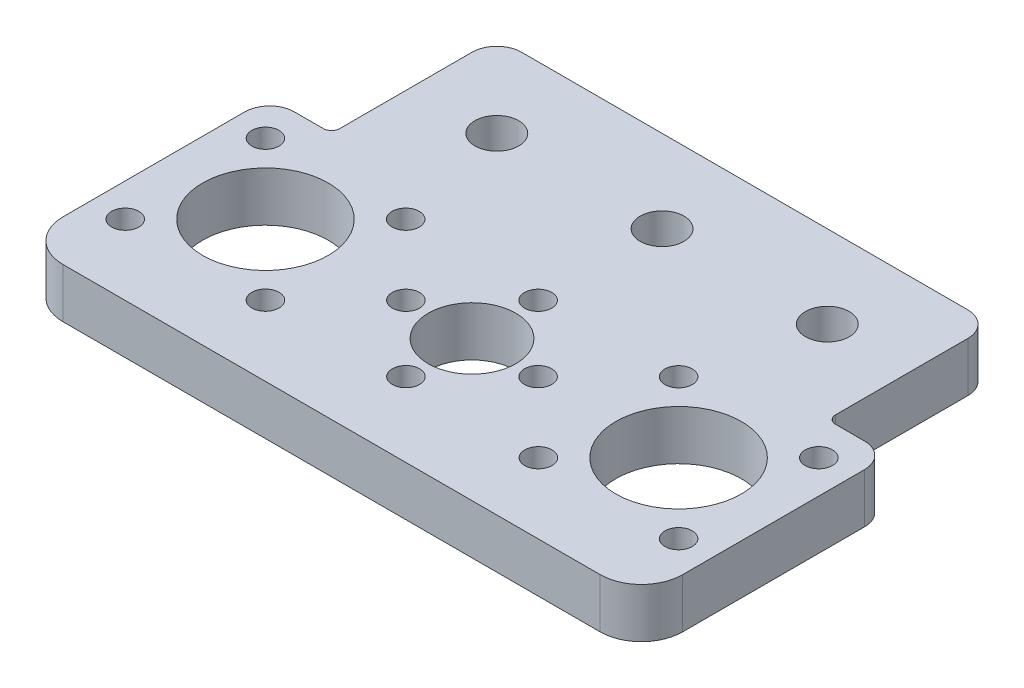
SolidWorks part; units mm, degrees
ref_plane "前视基准面" through (0, 0, 0) normal (0, 0, 1) x (1, 0, 0)
ref_plane "上视基准面" through (0, 0, 0) normal (0, 1, 0) x (1, 0, 0)
ref_plane "右视基准面" through (0, 0, 0) normal (1, 0, 0) x (0, 0, -1)
sketch "草图1" plane through (0, 0, 0) normal (0, 1, 0) x (1, 0, 0)
  line L0 (0, 80.2608) -> (0, -70.9317) construction
  line L1 (-25, 80.2608) -> (-25, -70.9317) construction
  line L2 (25, 80.2608) -> (25, -70.9317) construction
  line L3 (-49.3571, 0) -> (56.9138, 0) construction
  line L4 (-33.4853, 8.4853) -> (-16.5147, 8.4853) construction
  line L5 (-37.5, 28) -> (-37.5, -12)
  line L6 (37.5, 28) -> (37.5, -12)
  line L7 (-32.5, -17) -> (32.5, -17)
  line L8 (-49.3571, 13) -> (56.9138, 13) construction
  line L9 (-49.3571, 23) -> (56.9138, 23) construction
  line L10 (-20, 80.2608) -> (-20, -70.9317) construction
  line L11 (20, 80.2608) -> (20, -70.9317) construction
  line L12 (-32.5, 33) -> (32.5, 33)
  line L13 (-37.5, 80.2608) -> (-37.5, -70.9317) construction
  line L14 (-49.3571, -17) -> (56.9138, -17) construction
  line L15 (37.5, 80.2608) -> (37.5, -70.9317) construction
  line L16 (-49.3571, 33) -> (56.9138, 33) construction
  line L17 (-30, 80.2608) -> (-30, -70.9317) construction
  line L18 (30, 80.2608) -> (30, -70.9317) construction
  line L19 (30, 33) -> (30, 13)
  line L20 (30, 13) -> (37.5, 13)
  line L21 (-30, 33) -> (-30, 13)
  line L22 (-30, 13) -> (-37.5, 13)
  circle A0 centre (-25, 0) radius 7.6
  circle A1 centre (-25, 0) radius 12 construction
  circle A2 centre (-33.4853, 8.4853) radius 1.65
  circle A3 centre (-16.5147, 8.4853) radius 1.65
  circle A4 centre (-16.5147, -8.4853) radius 1.65
  circle A5 centre (-33.4853, -8.4853) radius 1.65
  circle A6 centre (16.5147, -8.4853) radius 1.65
  circle A7 centre (16.5147, 8.4853) radius 1.65
  circle A8 centre (33.4853, 8.4853) radius 1.65
  circle A9 centre (25, 0) radius 7.6
  circle A10 centre (33.4853, -8.4853) radius 1.65
  circle A11 centre (0, 0) radius 5.3
  circle A12 centre (0, 0) radius 8 construction
  circle A13 centre (0, 0) radius 11 construction
  circle A14 centre (0, 8) radius 1.65
  circle A15 centre (8, 0) radius 1.65
  circle A16 centre (0, -8) radius 1.65
  circle A17 centre (-8, 0) radius 1.65
  circle A18 centre (-20, 23) radius 2.65
  circle A19 centre (0, 23) radius 2.65
  circle A20 centre (20, 23) radius 2.65
  arc A21 (-37.5, -12) -> (-32.5, -17) centre (-32.5, -12) ccw
  arc A22 (32.5, -17) -> (37.5, -12) centre (32.5, -12) ccw
  arc A23 (37.5, 28) -> (32.5, 33) centre (32.5, 28) ccw
  arc A24 (-32.5, 33) -> (-37.5, 28) centre (-32.5, 28) ccw
  point P23 (-25, 0)
  point P50 (0, 0)
  dimension "D3" = 15.2
  dimension "D4" = 24
  dimension "D5" = 3.3
  dimension "D9" = 10.6
  dimension "D10" = 16
  dimension "D11" = 22
  dimension "D12" = 3.3
  dimension "D19" = 5.3
  dimension "D22" = 5
  dimension "D1" = 25
  dimension "D7" = 12.5
  dimension "D14" = 50
  dimension "D2" = 25
  dimension "D8" = 12.5
  dimension "D15" = 13
  dimension "D16" = 10
  dimension "D17" = 20
  dimension "D18" = 20
  dimension "D21" = 10
  dimension "D23" = 30
  dimension "D24" = 30
  dimension "D20" = 3
  dimension "D6" = 4
  dimension "D13" = 4
extrude "凸台-拉伸1" add sketch "草图1" along normal blind 6 contours L7 A22 L6 L20 L19 L12 L21 L22 L5 A21 A10 A8 A6 A5 A4 A3 A2 A0 A7 A9 A11 A14 A15 A16 A17 A18 A19 A20
fillet "圆角1" radius 3 4 edges at (30, 3, -33) (-30, 3, -33) (-37.5, 3, -13) (37.5, 3, -13)
fillet "圆角2" radius 1 2 edges at (30, 3, -13) (-30, 3, -13)
